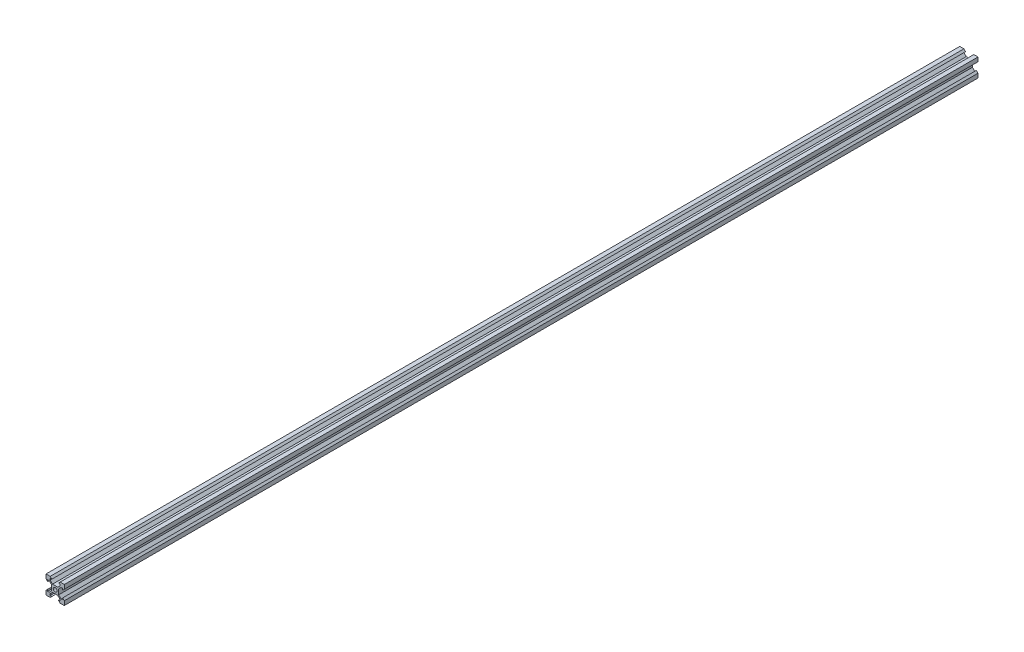
SolidWorks part; units mm, degrees
ref_plane "Front Plane" through (0, 0, 0) normal (0, 0, 1) x (1, 0, 0)
ref_plane "Top Plane" through (0, 0, 0) normal (0, 1, 0) x (1, 0, 0)
ref_plane "Right Plane" through (0, 0, 0) normal (1, 0, 0) x (0, 0, -1)
sketch "Sketch1" plane through (0, 0, 0) normal (0, 0, 1) x (1, 0, 0)
  line L0 (0, 35.0499) -> (0, -36.1787) construction
  line L1 (-41.2094, 0) -> (56.3924, 0) construction
  line L2 (5.42, -10) -> (10, -10)
  line L3 (5.42, 10) -> (3.62, 8.2)
  line L4 (3.62, 8.2) -> (5.5, 8.2)
  line L5 (5.5, 8.2) -> (5.5, 6.5606)
  line L6 (5.5, 6.5606) -> (2.8394, 3.9)
  line L7 (2.8394, 3.9) -> (-2.8394, 3.9)
  line L8 (5.42, 10) -> (10, 10)
  line L9 (2.8394, -3.9) -> (-2.8394, -3.9)
  line L10 (5.5, -6.5606) -> (2.8394, -3.9)
  line L11 (5.5, -8.2) -> (5.5, -6.5606)
  line L12 (3.62, -8.2) -> (5.5, -8.2)
  line L13 (5.42, -10) -> (3.62, -8.2)
  line L14 (0, 0) -> (10, -10) construction
  line L15 (3.9, -2.8394) -> (3.9, 0)
  line L16 (6.5606, -5.5) -> (3.9, -2.8394)
  line L17 (8.2, -5.5) -> (6.5606, -5.5)
  line L18 (8.2, -3.62) -> (8.2, -5.5)
  line L19 (10, -5.42) -> (8.2, -3.62)
  line L20 (10, -5.42) -> (10, -10)
  line L21 (0, 0) -> (10, 10) construction
  line L22 (10, 5.42) -> (10, 10)
  line L23 (3.9, 2.8394) -> (3.9, 0)
  line L24 (6.5606, 5.5) -> (3.9, 2.8394)
  line L25 (8.2, 5.5) -> (6.5606, 5.5)
  line L26 (8.2, 3.62) -> (8.2, 5.5)
  line L27 (10, 5.42) -> (8.2, 3.62)
  line L28 (0, 0) -> (-10, 10) construction
  line L29 (0, 0) -> (-10, -10) construction
  line L30 (-10, 5.42) -> (-8.2, 3.62)
  line L31 (-8.2, 3.62) -> (-8.2, 5.5)
  line L32 (-8.2, 5.5) -> (-6.5606, 5.5)
  line L33 (-6.5606, 5.5) -> (-3.9, 2.8394)
  line L34 (-3.9, 2.8394) -> (-3.9, 0)
  line L35 (-10, 5.42) -> (-10, 10)
  line L36 (-10, -5.42) -> (-10, -10)
  line L37 (-10, -5.42) -> (-8.2, -3.62)
  line L38 (-8.2, -3.62) -> (-8.2, -5.5)
  line L39 (-8.2, -5.5) -> (-6.5606, -5.5)
  line L40 (-6.5606, -5.5) -> (-3.9, -2.8394)
  line L41 (-3.9, -2.8394) -> (-3.9, 0)
  line L42 (-5.42, -10) -> (-3.62, -8.2)
  line L43 (-3.62, -8.2) -> (-5.5, -8.2)
  line L44 (-5.5, -8.2) -> (-5.5, -6.5606)
  line L45 (-5.5, -6.5606) -> (-2.8394, -3.9)
  line L46 (-5.42, 10) -> (-10, 10)
  line L47 (-5.5, 6.5606) -> (-2.8394, 3.9)
  line L48 (-5.5, 8.2) -> (-5.5, 6.5606)
  line L49 (-3.62, 8.2) -> (-5.5, 8.2)
  line L50 (-5.42, 10) -> (-3.62, 8.2)
  line L51 (-5.42, -10) -> (-10, -10)
  point P49 (0, -3.9)
  point P51 (0, 3.9)
  dimension "D1" = 10
  dimension "D3" = 4.58
  dimension "D4" = 45
  dimension "D5" = 1.8
  dimension "D6" = 4.3
  dimension "D7" = 5.5
  dimension "D8" = 2.8394
extrude "Boss-Extrude1" add sketch "Sketch1" along normal mid plane 1000
sketch "Sketch2" plane through (0, 0, 500) normal (0, 0, 1) x (1, 0, 0)
  circle A0 centre (0, 0) radius 2.1
  dimension "D1" = 4.2
extrude "Cut-Extrude1" cut sketch "Sketch2" against normal through all
